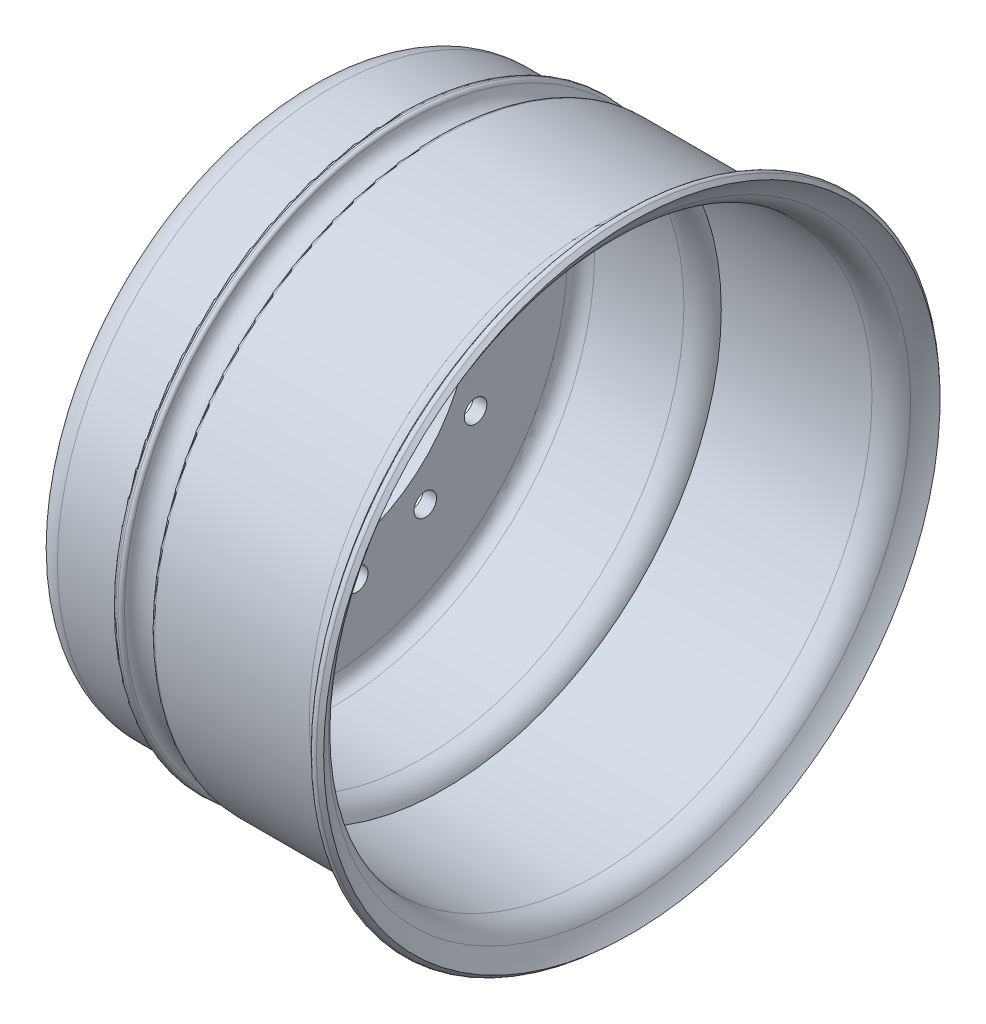
SolidWorks part; units mm, degrees
ref_plane "Front Plane" through (0, 0, 0) normal (0, 0, 1) x (1, 0, 0)
ref_plane "Top Plane" through (0, 0, 0) normal (0, 1, 0) x (1, 0, 0)
ref_plane "Right Plane" through (0, 0, 0) normal (1, 0, 0) x (0, 0, -1)
sketch "Sketch1" plane through (0, 0, 0) normal (0, 0, 1) x (1, 0, 0)
  line L0 (0, 0) -> (112.4686, 0) construction
  line L1 (0, 190) -> (6, 190)
  line L2 (26, 190) -> (131, 190)
  line L3 (0, 184) -> (1.1676, 184)
  line L4 (30.8324, 184) -> (131, 184)
  line L5 (151, 208.9038) -> (155.3992, 204.8238)
  line L6 (16, 174) -> (-43.4077, 174)
  line L7 (-52.4077, 165) -> (-52.4077, 100)
  line L8 (-52.4077, 100) -> (-61.4077, 100)
  line L9 (-61.4077, 100) -> (-61.4077, 165)
  line L10 (-43.4077, 183) -> (1.6125, 183)
  line L11 (0, 184) -> (0, 190)
  arc A0 (6, 190) -> (26, 190) centre (16, 190) ccw
  arc A1 (131, 190) -> (141.9127, 196.4038) centre (131, 202.5) ccw
  arc A2 (141.9127, 196.4038) -> (151, 208.9038) centre (198.6585, 164.7035) cw
  arc A3 (1.1676, 184) -> (1.6125, 183) centre (16, 190) ccw
  arc A4 (131, 184) -> (147.1507, 193.4776) centre (131, 202.5) ccw
  arc A5 (147.1507, 193.4776) -> (155.3992, 204.8238) centre (198.6585, 164.7035) cw
  arc A6 (-43.4077, 174) -> (-52.4077, 165) centre (-43.4077, 165) ccw
  arc A7 (-61.4077, 165) -> (-43.4077, 183) centre (-43.4077, 165) cw
  arc A8 (16, 174) -> (30.8324, 184) centre (16, 190) ccw
  arc A10 (1.1676, 184) -> (30.8324, 184) centre (16, 190) ccw construction
  dimension "D2" = 6
  dimension "D4" = 12.5
  dimension "D5" = 65
  dimension "D9" = 9
  dimension "D10" = 18
  dimension "D1" = 6
  dimension "D3" = 105
  dimension "D6" = 12.5
  dimension "D7" = 145
  dimension "D8" = 190
  dimension "D11" = 9
  dimension "D12" = 65
  dimension "D13" = 9
revolve "Revolve1" add sketch "Sketch1" angle 360 mid plane about L0
sketch "Sketch2" plane through (-61.4077, 0, 0) normal (-1, 0, 0) x (0, 0, 1)
  circle A0 centre (0, 120) radius 7.5
  dimension "D1" = 15
  dimension "D2" = 120
extrude "Cut-Extrude1" cut sketch "Sketch2" against normal through all
pattern_circular "CirPattern1" count 15 over 360 about axis through (0, 0, 0) along (1, 0, 0) of "Cut-Extrude1"
fillet "Fillet2" radius 2.5 4 edges at (0, 0, 190) (6, 0, 190) (151, 0, 208.9038) (26, 0, 190)
